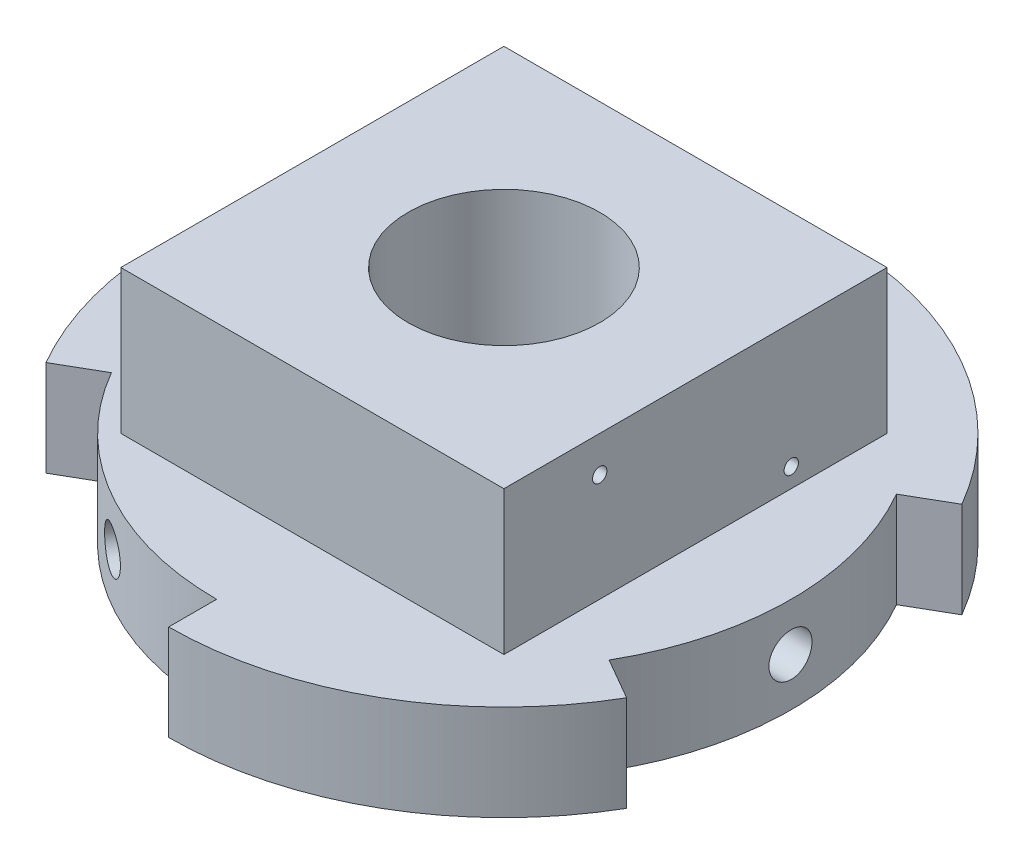
SolidWorks part; units mm, degrees
ref_plane "Front Plane" through (0, 0, 0) normal (0, 0, 1) x (1, 0, 0)
ref_plane "Top Plane" through (0, 0, 0) normal (0, 1, 0) x (1, 0, 0)
ref_plane "Right Plane" through (0, 0, 0) normal (1, 0, 0) x (0, 0, -1)
sketch "Sketch1" plane through (0, 0, 0) normal (0, 1, 0) x (1, 0, 0)
  line L0 (-30.3109, 17.5) -> (-25.9808, 15)
  line L1 (-30.3109, -17.5) -> (-25.9808, -15)
  line L2 (-30.3109, 17.5) -> (0, 0) construction
  line L3 (0, 0) -> (-30.3109, -17.5) construction
  line L4 (-0.4058, 0) -> (-50000.4058, 0) construction
  line L5 (30.3109, 17.5) -> (25.9808, 15)
  line L6 (0, 35) -> (0, 30)
  line L7 (0, -35) -> (0, -30)
  line L8 (30.3109, -17.5) -> (25.9808, -15)
  arc A1 (-30.3109, 17.5) -> (-30.3109, -17.5) centre (0, 0) ccw
  arc A3 (30.3109, 17.5) -> (0, 35) centre (0, 0) ccw
  circle A4 centre (0, 0) radius 30
  arc A5 (0, -35) -> (30.3109, -17.5) centre (0, 0) ccw
  point P5 (-35, 0)
  point P23 (0, 0)
  dimension "D1" = 35
  dimension "D5" = 60
  dimension "D2" = 5
  dimension "D3" = 60
  dimension "D4" = 3
extrude "Boss-Extrude3" add sketch "Sketch1" along normal blind 10 contours A4 L0 A1 L1 | A4 | A4 L5 A3 L6 | L7 A5 L8 A4
ref_plane "Plane1" through (40, 0, 0) normal (1, 0, 0) x (0, 0, -1)
sketch "Sketch2" plane through (40, 0, 0) normal (1, 0, 0) x (0, 0, -1)
  line L0 (-15, 10) -> (15, 0) construction
  line L1 (15, 10) -> (-15, 0) construction
  circle A0 centre (0, 5) radius 2.25
  dimension "D1" = 4.5
extrude "Cut-Extrude1" cut sketch "Sketch2" against normal blind 25
pattern_circular "CirPattern1" count 3 over 360 about axis through (0, 0, 0) along (0, 1, 0) of "Cut-Extrude1"
sketch "Sketch3" plane through (0, 10, 0) normal (0, 1, 0) x (1, 0, 0)
  line L1 (20, -20) -> (-20, -20)
  line L2 (20, -20) -> (20, 20)
  line L3 (20, 20) -> (-20, 20)
  line L4 (-20, -20) -> (-20, 20)
  line L5 (20, -20) -> (-20, 20) construction
  line L6 (20, 20) -> (-20, -20) construction
  point P0 (0, 0)
  dimension "D1" = 40
  dimension "D2" = 40
extrude "Boss-Extrude4" add sketch "Sketch3" along normal blind 15
sketch "Sketch4" plane through (20, 0, 0) normal (1, 0, 0) x (0, 0, -1)
  line L0 (0, 25) -> (0, 10) construction
  line L1 (-20, 25) -> (20, 25) construction
  line L2 (-20, 10) -> (20, 10) construction
  line L3 (10, 10) -> (10, 12) construction
  line L4 (10, 10) -> (20, 10) construction
  line L7 (-10, 25) -> (-10, 21.25) construction
  line L8 (10, 25) -> (10, 25.0788) construction
  circle A0 centre (-10, 21.25) radius 0.75
  circle A1 centre (10, 12) radius 0.75
  point P11 (-10, 23.125)
  dimension "D1" = 1.5
  dimension "D2" = 1.5
  dimension "D3" = 10
  dimension "D4" = 20
  dimension "D5" = 3.75
  dimension "D6" = 2
sketch "Sketch5" plane through (0, 25, 0) normal (0, 1, 0) x (1, 0, 0)
  circle A0 centre (0, 0) radius 10
  dimension "D1" = 20
extrude "Cut-Extrude5" cut sketch "Sketch5" against normal up to surface (25 mm away) up to face at (0, 0, 0)
extrude "Cut-Extrude6" cut sketch "Sketch4" against normal blind 6 contours A0 | A1
pattern_circular "CirPattern2" count 2 over 360 about axis through (0, -28.2843, 0) along (0, 1, 0) of "Cut-Extrude6"
sketch "Sketch6" plane through (0, 10, 0) normal (0, 1, 0) x (1, 0, 0)
  line L0 (0, 20) -> (0, 30) construction
  line L1 (20, 20) -> (-20, 20) construction
